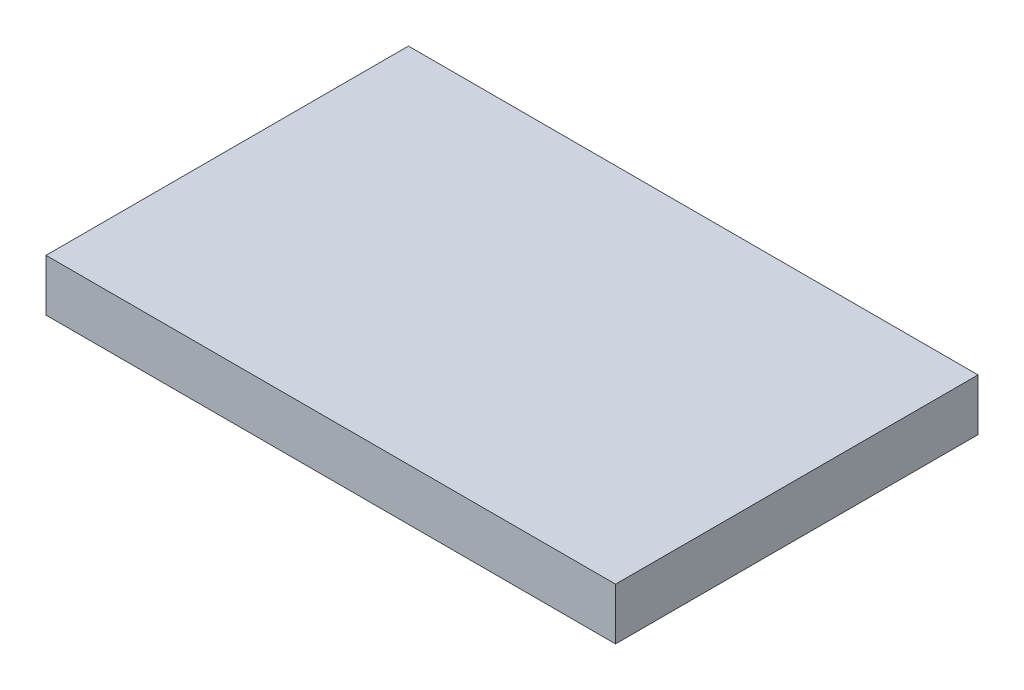
SolidWorks part; units mm, degrees
material "ABS"
ref_plane "Front Plane" through (0, 0, 0) normal (0, 0, 1) x (1, 0, 0)
ref_plane "Top Plane" through (0, 0, 0) normal (0, 1, 0) x (1, 0, 0)
ref_plane "Right Plane" through (0, 0, 0) normal (1, 0, 0) x (0, 0, -1)
sketch "Sketch1" plane through (0, 0, 0) normal (0, 1, 0) x (1, 0, 0)
  line L1 (-279.4, -203.2) -> (279.4, -203.2)
  line L2 (-279.4, -203.2) -> (-279.4, 203.2)
  line L3 (-279.4, 203.2) -> (279.4, 203.2)
  line L4 (279.4, -203.2) -> (279.4, 203.2)
  line L5 (-279.4, -203.2) -> (279.4, 203.2) construction
  line L6 (-279.4, 203.2) -> (279.4, -203.2) construction
  line L7 (-152.4, 203.2) -> (152.4, 203.2)
  line L8 (-152.4, 203.2) -> (-152.4, 12.7)
  line L9 (-152.4, 12.7) -> (152.4, 12.7)
  line L10 (152.4, 203.2) -> (152.4, 12.7)
  point P0 (0, 0)
  dimension "D1" = 558.8
  dimension "D2" = 406.4
  dimension "D3" = 127
  dimension "D4" = 127
  dimension "D5" = 190.5
extrude "Boss-Extrude1" add sketch "Sketch1" along normal blind 25.4 contours L3 L10 L9 L8 L2 L1 L4
fillet "Fillet1" radius 20.32 4 edges at (279.4, 12.7, -203.2) (152.4, 12.7, -203.2) (-279.4, 12.7, -203.2) (-152.4, 12.7, -203.2)
shell "Shell1" thickness 2.54
sketch "Sketch2" plane through (0, 25.4, 0) normal (0, 1, 0) x (1, 0, 0)
  line L0 (-317.2722, 165.1) -> (360.7838, 165.1) construction
  line L1 (-279.4, -203.2) -> (279.4, -203.2) construction
  line L2 (152.4, 182.88) -> (152.4, 12.7) construction
  line L3 (-152.4, 182.88) -> (-152.4, 12.7) construction
  circle A0 centre (-177.72, 165.1) radius 2.54
  circle A1 centre (-167.56, 165.1) radius 2.54
  circle A2 centre (167.56, 165.1) radius 2.54
  circle A3 centre (177.72, 165.1) radius 2.54
  point P12 (157.4, 165.1)
  point P13 (-157.4, 165.1)
  dimension "D2" = 10.16
  dimension "D8" = 5.08
  dimension "D1" = 368.3
  dimension "D3" = 10.16
  dimension "D4" = 10.16
  dimension "D5" = 10.16
  dimension "D6" = 5
  dimension "D7" = 5
extrude "Cut-Extrude1" cut sketch "Sketch2" against normal through all
sketch "Sketch3" plane through (0, 25.4, 0) normal (0, 1, 0) x (1, 0, 0)
  line L0 (279.4, -25.4) -> (279.4, 212.6309)
  line L1 (279.4, -203.2) -> (0, -203.2)
  line L2 (279.4, -203.2) -> (279.4, -25.4)
  line L3 (279.4, -25.4) -> (0, -25.4)
  line L4 (0, -203.2) -> (0, -25.4)
  line L5 (279.4, 212.6309) -> (-301.5476, 212.6309)
  line L6 (-301.5476, 212.6309) -> (-301.5476, -203.2)
  line L7 (-301.5476, -203.2) -> (0, -203.2)
  circle M3 centre (-177.72, 165.1) radius 2.54
  circle M4 centre (-167.56, 165.1) radius 2.54
  circle M5 centre (167.56, 165.1) radius 2.54
  circle M6 centre (177.72, 165.1) radius 2.54
  line M7 (279.4, -203.2) -> (279.4, 182.88)
  arc M8 (279.4, 182.88) -> (259.08, 203.2) centre (259.08, 182.88) ccw
  line M9 (259.08, 203.2) -> (172.72, 203.2)
  arc M10 (172.72, 203.2) -> (152.4, 182.88) centre (172.72, 182.88) ccw
  line M11 (152.4, 182.88) -> (152.4, 12.7)
  line M12 (152.4, 12.7) -> (-152.4, 12.7)
  line M13 (-152.4, 12.7) -> (-152.4, 182.88)
  arc M14 (-152.4, 182.88) -> (-172.72, 203.2) centre (-172.72, 182.88) ccw
  line M15 (-172.72, 203.2) -> (-259.08, 203.2)
  arc M16 (-259.08, 203.2) -> (-279.4, 182.88) centre (-259.08, 182.88) ccw
  line M17 (-279.4, 182.88) -> (-279.4, -203.2)
  line M18 (-279.4, -203.2) -> (279.4, -203.2)
  dimension "D1" = 279.4
  dimension "D2" = 177.8
extrude "Cut-Extrude2" cut sketch "Sketch3" against normal through all contours L4 L3 M18 M7 M8 M9 M10 M11 M12 M13 M14 M15 M16 M17 M4 M6 M5 M3
